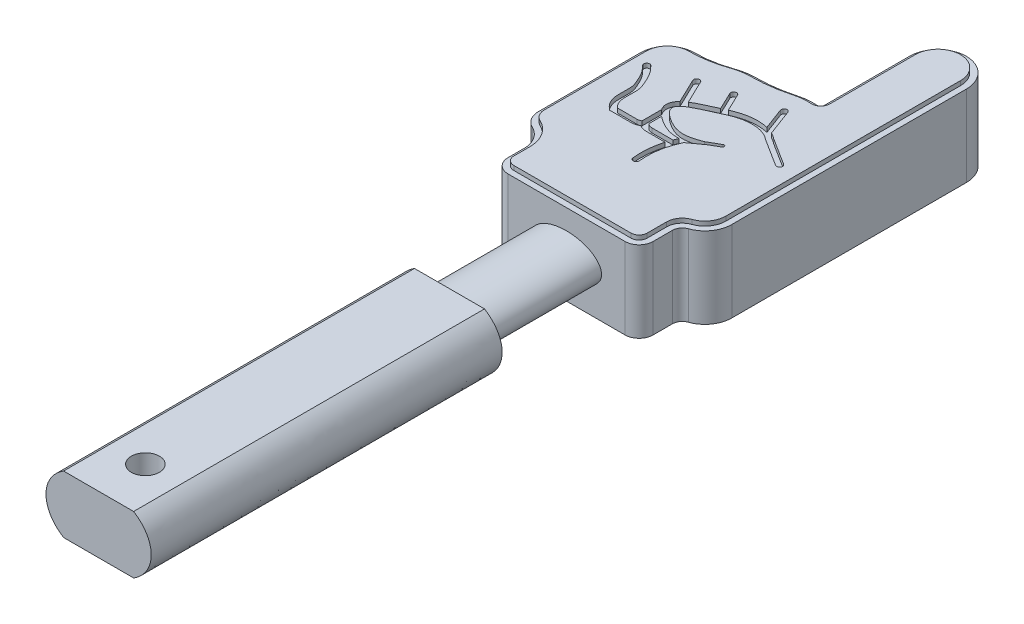
SolidWorks part; units mm, degrees
ref_plane "Plan de face" through (0, 0, 0) normal (0, 0, 1) x (1, 0, 0)
ref_plane "Plan de dessus" through (0, 0, 0) normal (0, 1, 0) x (1, 0, 0)
ref_plane "Plan de droite" through (0, 0, 0) normal (1, 0, 0) x (0, 0, -1)
sketch "Esquisse2" plane through (0, 0, 0) normal (0, 1, 0) x (1, 0, 0)
  line L4 (-461.3514, 50.6784) -> (-461.3514, 90.7755)
  line L5 (-471.0713, 90.7755) -> (-471.0713, 76.1755)
  line L6 (-465.5648, 44.7364) -> (-465.5648, 41.4326)
  line L7 (-467.9625, 39.035) -> (-487.9825, 39.035)
  line L8 (-490.3801, 41.4326) -> (-490.3801, 44.1985)
  line L9 (-494.5966, 50.8393) -> (-494.5966, 68.3008)
  arc A17 (-461.3514, 90.7755) -> (-471.0713, 90.7755) centre (-466.2114, 90.7755) ccw
  arc A18 (-471.0713, 76.1755) -> (-471.6659, 75.6215) centre (-471.6268, 76.1755) cw
  arc A19 (-471.6659, 75.6215) -> (-474.8438, 75.3021) centre (-472.3289, 66.2484) ccw
  arc A20 (-461.3514, 50.6784) -> (-464.4333, 46.3321) centre (-465.9571, 50.6784) cw
  arc A21 (-464.4333, 46.3321) -> (-465.5648, 44.7364) centre (-463.8739, 44.7364) ccw
  arc A22 (-465.5648, 41.4326) -> (-467.9625, 39.035) centre (-467.9625, 41.4326) cw
  arc A23 (-487.9825, 39.035) -> (-490.3801, 41.4326) centre (-487.9825, 41.4326) cw
  arc A24 (-490.3801, 44.1985) -> (-492.803, 48.0144) centre (-494.5966, 44.1985) ccw
  arc A25 (-492.803, 48.0144) -> (-494.5966, 50.8393) centre (-491.4751, 50.8393) cw
  arc A26 (-494.5966, 68.3008) -> (-489.9856, 72.9117) centre (-489.9856, 68.3008) cw
  arc A27 (-489.9856, 72.9117) -> (-484.1893, 73.9115) centre (-489.9856, 90.214) ccw
  arc A28 (-484.1893, 73.9115) -> (-480.9635, 74.4679) centre (-480.9635, 64.8387) cw
  arc A29 (-480.9635, 74.4679) -> (-474.8438, 75.3021) centre (-480.9635, 97.3326) ccw
  dimension "D3" = 14.6
  dimension "D4" = 0.5554
  dimension "D5" = 9.3965
  dimension "D6" = 4.6057
  dimension "D7" = 1.6909
  dimension "D8" = 2.3977
  dimension "D9" = 4.2164
  dimension "D10" = 3.1214
  dimension "D11" = 4.6109
  dimension "D12" = 17.3023
  dimension "D13" = 9.6292
  dimension "D1" = 9.72
  dimension "D2" = 461.3514
  dimension "D15" = 472.3289
  dimension "D16" = 465.5648
  dimension "D17" = 480.9635
  dimension "D18" = 484.1893
  dimension "D19" = 72.9117
  dimension "D21" = 50.8393
  dimension "D22" = 50.6784
  dimension "D36" = 39.035
extrude "Boss.-Extru.1" add sketch "Esquisse2" along normal blind 14.6
sketch "Esquisse4" plane through (0, 14.6, 0) normal (0, 1, 0) x (1, 0, 0)
  line L0 (-472.4313, 71.3413) -> (-470.759, 66.8763)
  line L1 (-479.2673, 69.577) -> (-477.8287, 66.5691)
  line L2 (-484.8272, 68.1421) -> (-483.1754, 64.6884)
  line L3 (-487.6052, 57.4055) -> (-484.2817, 57.4055)
  line L5 (-478.1514, 57.4055) -> (-481.7388, 57.4055)
  line L6 (-490.4583, 65.8897) -> (-491.0481, 66.5366)
  line L7 (-491.0481, 66.5366) -> (-472.4313, 71.3413) construction
  line L8 (-461.3514, 50.6784) -> (-461.3514, 90.7755) construction
  line L9 (-473.3677, 70.9906) -> (-471.9932, 67.3203)
  line L10 (-480.1694, 69.1456) -> (-478.7397, 66.1562)
  line L12 (-491.1972, 65.2159) -> (-491.787, 65.8628)
  line L13 (-487.9601, 56.4055) -> (-484.2783, 56.4055)
  line L14 (-477.4426, 56.4055) -> (-481.7388, 56.4055)
  line L16 (-483.1205, 57.4055) -> (-483.1205, 61.028) construction
  line L17 (-483.6205, 57.5979) -> (-483.6205, 60.9564)
  line L18 (-484.8272, 68.1421) -> (-482.7323, 63.7919) construction
  line L19 (-484.3767, 68.359) -> (-482.4341, 64.3251)
  line L20 (-485.2777, 67.9251) -> (-483.2443, 63.7026)
  line L21 (-470.3753, 65.4409) -> (-465.3514, 62.8537) construction
  line L22 (-469.8136, 66.2662) -> (-465.0842, 63.2763)
  line L23 (-470.348, 65.421) -> (-465.6185, 62.4311)
  line L24 (-473.0349, 60.7918) -> (-475.4776, 59.3877) construction
  line L25 (-472.8992, 60.5556) -> (-474.5084, 59.6306)
  line L26 (-473.1707, 61.028) -> (-475.2006, 59.8612)
  line L27 (-482.6205, 57.7552) -> (-482.6205, 59.9234)
  arc A0 (-484.2817, 57.4055) -> (-483.6205, 57.5979) centre (-484.2916, 58.6719) ccw
  arc A1 (-476.8297, 57.9491) -> (-477.9359, 51.4698) centre (-466.0442, 52.7736) ccw
  arc A3 (-481.7388, 57.4055) -> (-482.6205, 57.7552) centre (-481.7388, 58.692) cw
  arc A5 (-484.2783, 56.4055) -> (-483.0183, 56.797) centre (-484.2916, 58.6719) ccw
  arc A6 (-481.7388, 56.4055) -> (-483.0183, 56.797) centre (-481.7388, 58.692) cw
  arc A7 (-477.8343, 58.1619) -> (-478.1514, 57.4055) centre (-466.0442, 52.7736) ccw
  arc A8 (-472.4313, 71.3413) -> (-473.3677, 70.9906) centre (-472.8995, 71.1659) ccw
  arc A10 (-479.2673, 69.577) -> (-480.1694, 69.1456) centre (-479.7183, 69.3613) ccw
  arc A14 (-491.0481, 66.5366) -> (-491.787, 65.8628) centre (-491.4176, 66.1997) ccw
  arc A18 (-470.4025, 65.4609) -> (-470.348, 65.421) centre (-470.3753, 65.4409) ccw
  arc A19 (-477.9359, 51.4698) -> (-478.93, 51.3609) centre (-478.433, 51.4154) cw
  arc A21 (-484.3767, 68.359) -> (-485.2777, 67.9251) centre (-484.8272, 68.1421) ccw
  arc A23 (-470.4025, 65.4609) -> (-470.348, 65.421) centre (-470.3753, 65.4409) ccw
  arc A24 (-465.6185, 62.4311) -> (-465.0842, 63.2763) centre (-465.3514, 62.8537) ccw
  arc A25 (-472.8992, 60.5556) -> (-473.1707, 61.028) centre (-473.0349, 60.7918) ccw
  arc A27 (-478.488, 56.4055) -> (-478.93, 51.3609) centre (-466.0442, 52.7736) ccw
  spline S0 degree 3 poles (-490.4583, 65.8897) (-489.9643, 65.3478) (-489.2576, 64.0084) (-488.0431, 61.1753) (-489.0579, 58.5852) (-487.6052, 57.4055) knots 0 0 0 0 0.249547 0.474449 1 1 1 1
  spline S1 degree 3 poles (-483.1823, 64.7264) (-483.18, 64.7137) (-483.1777, 64.7011) (-483.1754, 64.6884) knots 0.246141 0.246141 0.246141 0.246141 0.248714 0.248714 0.248714 0.248714
  spline S2 degree 3 poles (-470.4025, 65.4609) (-471.657, 66.5152) (-475.3225, 66.8063) (-478.8719, 64.9069) (-484.364, 62.5575) (-480.7126, 59.6038) (-478.2259, 58.8088) (-475.901, 59.5831) (-475.2006, 59.8612) knots 0 0 0 0 0.163612 0.32751 0.477242 0.563601 0.697734 0.765481 0.765481 0.765481 0.765481
  spline S3 degree 2 poles (-474.5084, 59.6306) (-475.3996, 58.9745) (-476.8297, 57.9491) knots 0.955294 0.955294 0.955294 1 1 1
  spline S4 degree 3 poles (-483.2443, 63.7026) (-483.4189, 63.536) (-483.7603, 63.1422) (-484.042, 62.4144) (-483.9809, 61.7052) (-483.8197, 61.2849) (-483.6856, 61.0541) (-483.6205, 60.9564) knots 0.428302 0.428302 0.428302 0.428302 0.447364 0.468667 0.479319 0.48997 0.498689 0.498689 0.498689 0.498689
  spline S5 degree 3 poles (-478.7397, 66.1562) (-478.841, 66.109) (-479.3545, 65.8687) (-480.3361, 65.4112) (-481.5724, 64.8367) (-482.2436, 64.4471) (-482.4341, 64.3251) knots 0.287644 0.287644 0.287644 0.287644 0.298243 0.340849 0.383455 0.401257 0.401257 0.401257 0.401257
  spline S6 degree 3 poles (-491.1972, 65.2159) (-491.0951, 65.1039) (-490.914, 64.8749) (-490.5473, 64.3017) (-490.1129, 63.4322) (-489.672, 62.4162) (-489.5049, 61.5865) (-489.5458, 60.4567) (-489.5779, 59.3459) (-489.4093, 58.37) (-489.1649, 57.7435) (-488.8551, 57.2619) (-488.58, 56.9296) (-488.2037, 56.5974) (-488.0493, 56.478) (-487.9601, 56.4055) knots 0 0 0 0 0.064576 0.129153 0.258306 0.387458 0.516611 0.645764 0.774917 0.839493 0.90407 0.936358 0.968646 1.000934 1.033223 1.033223 1.033223 1.033223
  spline S7 degree 3 poles (-471.9932, 67.3203) (-472.1805, 67.365) (-473.344, 67.5872) (-475.4797, 67.4725) (-477.0435, 66.9088) (-477.8287, 66.5691) knots 0.068798 0.068798 0.068798 0.068798 0.085212 0.170424 0.255222 0.255222 0.255222 0.255222
  spline S8 degree 3 poles (-469.7591, 66.2264) (-470.0622, 66.4812) (-470.4037, 66.6993) (-470.759, 66.8763) knots 0 0 0 0 0.03228 0.03228 0.03228 0.03228
  spline S9 degree 3 poles (-482.6205, 59.9234) (-482.4376, 59.7779) (-481.8068, 59.3219) (-480.7516, 58.706) (-479.3663, 58.2092) (-478.3366, 58.1325) (-477.8343, 58.1619) knots 0.535686 0.535686 0.535686 0.535686 0.553879 0.596485 0.639091 0.681698 0.681698 0.681698 0.681698
  point P38 (-483.7797, 65.967)
  point P58 (-483.1205, 59.2167)
  point P61 (-474.2563, 60.0898)
  point P67 (-467.7161, 64.3487)
  dimension "D4" = 1.2865
  dimension "D6" = 4.6928
  dimension "D9" = 2.2865
  dimension "D10" = 11.0799
  dimension "D11" = 11.1625
  dimension "D13" = 13.661
  dimension "D1" = 1.2664
  dimension "D2" = 11.963
  dimension "D5" = 0.5
  dimension "D7" = 2.2664
  dimension "D12" = 0.0338
  dimension "D15" = 0.2724
  dimension "D8" = 1
  dimension "D14" = 15.4783
  dimension "D16" = 16.0443
  dimension "D17" = 3.7328
  dimension "D18" = 16.5846
  dimension "D19" = 17.9159
  dimension "D20" = 18.1649
  dimension "D21" = 1
  dimension "D22" = 20.3874
  dimension "D23" = 21.6423
  dimension "D24" = 4
  dimension "D25" = 21.824
  dimension "D26" = 5.1377
  dimension "D27" = 4.2671
  dimension "D28" = 23.4758
  dimension "D29" = 26.2538
  dimension "D30" = 27.0797
  dimension "D31" = 27.2299
  dimension "D32" = 27.9056
  dimension "D33" = 29.1069
  dimension "D34" = 29.6967
  dimension "D35" = 12.8812
  dimension "D36" = 13.8294
  dimension "D37" = 6.3647
  dimension "D38" = 8.4077
  dimension "D39" = 17.6054
  dimension "D40" = 18.3562
  dimension "D41" = 8.4623
  dimension "D42" = 9.0239
  dimension "D43" = 19.5575
  dimension "D44" = 11.5481
  dimension "D45" = 16.0912
  dimension "D46" = 9.4077
  dimension "D47" = 10.6418
  dimension "D48" = 11.5478
  dimension "D49" = 18.3669
  dimension "D50" = 11.6836
  dimension "D51" = 11.8193
  dimension "D52" = 21.2691
  dimension "D53" = 12.9049
  dimension "D54" = 13.157
  dimension "D55" = 13.8492
  dimension "D56" = 21.6669
  dimension "D57" = 16.4773
  dimension "D58" = 16.4829
  dimension "D59" = 23.0253
  dimension "D60" = 30.0662
  dimension "D61" = 12.8846
  dimension "D62" = 17.3883
  dimension "D63" = 16.099
  dimension "D64" = 12.3497
  dimension "D65" = 18.3943
  dimension "D66" = 19.8742
  dimension "D67" = 21.0827
  dimension "D70" = 21.7691
  dimension "D71" = 21.8309
  dimension "D72" = 21.8929
  dimension "D73" = 13.5913
  dimension "D74" = 22.4283
  dimension "D75" = 13.7576
  dimension "D79" = 15.6533
  dimension "D80" = 26.6087
  dimension "D84" = 18.0165
  dimension "D90" = 19.8943
  dimension "D92" = 20.076
extrude "Cut-Extrude1" cut sketch "Esquisse4" against normal blind 0.75
sketch "Sketch1" plane through (0, 14.6, 0) normal (0, 1, 0) x (1, 0, 0)
  line L0 (-462.3514, 50.6784) -> (-462.3514, 90.7755)
  line L1 (-470.0713, 90.7755) -> (-470.0713, 76.1755)
  line L2 (-493.5966, 68.3008) -> (-493.5966, 50.8393)
  line L3 (-489.3801, 44.1985) -> (-489.3801, 41.4326)
  line L4 (-487.9825, 40.035) -> (-467.9625, 40.035)
  line L5 (-466.5648, 41.4326) -> (-466.5648, 44.7364)
  line L6 (-461.3514, 50.6784) -> (-461.3514, 90.7755)
  line L7 (-471.0713, 90.7755) -> (-471.0713, 76.1755)
  line L8 (-494.5966, 68.3008) -> (-494.5966, 50.8393)
  line L9 (-490.3801, 44.1985) -> (-490.3801, 41.4326)
  line L10 (-487.9825, 39.035) -> (-467.9625, 39.035)
  line L11 (-465.5648, 41.4326) -> (-465.5648, 44.7364)
  line L12 (-461.3514, 50.6784) -> (-461.3514, 90.7755)
  line L13 (-471.0713, 90.7755) -> (-471.0713, 76.1755)
  line L14 (-494.5966, 68.3008) -> (-494.5966, 50.8393)
  line L15 (-490.3801, 44.1985) -> (-490.3801, 41.4326)
  line L16 (-487.9825, 39.035) -> (-467.9625, 39.035)
  line L17 (-465.5648, 41.4326) -> (-465.5648, 44.7364)
  arc A0 (-464.7642, 47.2758) -> (-462.3514, 50.6784) centre (-465.9571, 50.6784) ccw
  arc A1 (-462.3514, 90.7755) -> (-470.0713, 90.7755) centre (-466.2114, 90.7755) ccw
  arc A2 (-471.7365, 74.624) -> (-470.0713, 76.1755) centre (-471.6268, 76.1755) ccw
  arc A3 (-471.7365, 74.624) -> (-474.5762, 74.3386) centre (-472.3289, 66.2484) ccw
  arc A4 (-480.9635, 73.4679) -> (-474.5762, 74.3386) centre (-480.9635, 97.3326) ccw
  arc A5 (-480.9635, 73.4679) -> (-483.8543, 72.9693) centre (-480.9635, 64.8387) ccw
  arc A6 (-489.9856, 71.9117) -> (-483.8543, 72.9693) centre (-489.9856, 90.214) ccw
  arc A7 (-489.9856, 71.9117) -> (-493.5966, 68.3008) centre (-489.9856, 68.3008) ccw
  arc A8 (-493.5966, 50.8393) -> (-492.3776, 48.9194) centre (-491.4751, 50.8393) ccw
  arc A9 (-489.3801, 44.1985) -> (-492.3776, 48.9194) centre (-494.5966, 44.1985) ccw
  arc A10 (-489.3801, 41.4326) -> (-487.9825, 40.035) centre (-487.9825, 41.4326) ccw
  arc A11 (-467.9625, 40.035) -> (-466.5648, 41.4326) centre (-467.9625, 41.4326) ccw
  arc A12 (-464.7642, 47.2758) -> (-466.5648, 44.7364) centre (-463.8739, 44.7364) ccw
  arc A13 (-464.4333, 46.3321) -> (-461.3514, 50.6784) centre (-465.9571, 50.6784) ccw
  arc A14 (-461.3514, 90.7755) -> (-471.0713, 90.7755) centre (-466.2114, 90.7755) ccw
  arc A15 (-471.6659, 75.6215) -> (-471.0713, 76.1755) centre (-471.6268, 76.1755) ccw
  arc A16 (-471.6659, 75.6215) -> (-474.8438, 75.3021) centre (-472.3289, 66.2484) ccw
  arc A17 (-480.9635, 74.4679) -> (-474.8438, 75.3021) centre (-480.9635, 97.3326) ccw
  arc A18 (-480.9635, 74.4679) -> (-484.1893, 73.9115) centre (-480.9635, 64.8387) ccw
  arc A19 (-489.9856, 72.9117) -> (-484.1893, 73.9115) centre (-489.9856, 90.214) ccw
  arc A20 (-489.9856, 72.9117) -> (-494.5966, 68.3008) centre (-489.9856, 68.3008) ccw
  arc A21 (-494.5966, 50.8393) -> (-492.803, 48.0144) centre (-491.4751, 50.8393) ccw
  arc A22 (-490.3801, 44.1985) -> (-492.803, 48.0144) centre (-494.5966, 44.1985) ccw
  arc A23 (-490.3801, 41.4326) -> (-487.9825, 39.035) centre (-487.9825, 41.4326) ccw
  arc A24 (-467.9625, 39.035) -> (-465.5648, 41.4326) centre (-467.9625, 41.4326) ccw
  arc A25 (-464.4333, 46.3321) -> (-465.5648, 44.7364) centre (-463.8739, 44.7364) ccw
  arc A26 (-464.4333, 46.3321) -> (-461.3514, 50.6784) centre (-465.9571, 50.6784) ccw
  arc A27 (-461.3514, 90.7755) -> (-471.0713, 90.7755) centre (-466.2114, 90.7755) ccw
  arc A28 (-471.6659, 75.6215) -> (-471.0713, 76.1755) centre (-471.6268, 76.1755) ccw
  arc A29 (-471.6659, 75.6215) -> (-474.8438, 75.3021) centre (-472.3289, 66.2484) ccw
  arc A30 (-480.9635, 74.4679) -> (-474.8438, 75.3021) centre (-480.9635, 97.3326) ccw
  arc A31 (-480.9635, 74.4679) -> (-484.1893, 73.9115) centre (-480.9635, 64.8387) ccw
  arc A32 (-489.9856, 72.9117) -> (-484.1893, 73.9115) centre (-489.9856, 90.214) ccw
  arc A33 (-489.9856, 72.9117) -> (-494.5966, 68.3008) centre (-489.9856, 68.3008) ccw
  arc A34 (-494.5966, 50.8393) -> (-492.803, 48.0144) centre (-491.4751, 50.8393) ccw
  arc A35 (-490.3801, 44.1985) -> (-492.803, 48.0144) centre (-494.5966, 44.1985) ccw
  arc A36 (-490.3801, 41.4326) -> (-487.9825, 39.035) centre (-487.9825, 41.4326) ccw
  arc A37 (-467.9625, 39.035) -> (-465.5648, 41.4326) centre (-467.9625, 41.4326) ccw
  arc A38 (-464.4333, 46.3321) -> (-465.5648, 44.7364) centre (-463.8739, 44.7364) ccw
  dimension "D1" = 0
  dimension "D2" = 1
extrude "Cut-Extrude2" cut sketch "Sketch1" against normal blind 0.75
sketch "Sketch3" plane through (0, 0, -39.035) normal (0, 0, 1) x (1, 0, 0)
  line L0 (-487.9825, 13.85) -> (-467.9625, 13.85) construction
  line L1 (-487.9825, 13.85) -> (-487.9825, 0) construction
  ellipse E0 centre (-477.9825, 6.925) end of major axis (-483.9825, 6.925) minor radius 3.5
  point P1 (-472.0851, 6.925)
  point P7 (-477.9825, 3.2328)
  dimension "D1" = 6.925
  dimension "D2" = 10
  dimension "D3" = 7
  dimension "D4" = 12
extrude "Boss-Extrude1" add sketch "Sketch3" along normal blind 20
sketch "Sketch4" plane through (0, 0, -19.035) normal (0, 0, 1) x (1, 0, 0)
  line L0 (-471.9948, 11.85) -> (-483.9702, 11.85)
  line L2 (-483.9702, 2) -> (-471.9948, 2)
  line L4 (-487.9825, 0) -> (-467.9625, 0) construction
  line L5 (-487.9825, 13.85) -> (-467.9625, 13.85) construction
  spline S0 degree 3 poles (-468.9825, 6.6655) (-468.9825, 7.4441) (-469.0613, 7.9493) (-469.2911, 8.6876) (-469.3866, 8.9297) (-469.6081, 9.3925) (-469.7346, 9.6152) (-470.0172, 10.0444) (-470.1743, 10.2518) (-470.5098, 10.6425) (-470.6884, 10.8265) (-471.254, 11.3483) (-471.6739, 11.6572) (-472.549, 12.1865) (-473.0071, 12.4102) (-473.9577, 12.7896) (-474.4523, 12.9451) (-475.9405, 13.3093) (-476.9509, 13.4246) (-478.4914, 13.4252) (-479.0046, 13.3955) (-480.0155, 13.2773) (-480.5156, 13.1888) (-481.5037, 12.9476) (-481.9939, 12.7943) (-482.9511, 12.4135) (-483.4109, 12.1891) (-484.0672, 11.7928) (-484.2804, 11.6507) (-484.6942, 11.3436) (-484.8944, 11.1788) (-485.4603, 10.6577) (-485.7964, 10.2723) (-486.3679, 9.4084) (-486.5908, 8.9479) (-486.8211, 8.2181) (-486.8808, 7.9663) (-486.9612, 7.4547) (-486.9815, 7.1991) (-486.9834, 6.6879) (-486.965, 6.4323) (-486.8886, 5.9215) (-486.8304, 5.6677) (-486.6793, 5.1772) (-486.586, 4.9383) (-486.3652, 4.4729) (-486.237, 4.2457) (-485.9548, 3.8152) (-485.8002, 3.6103) (-485.4663, 3.2195) (-485.2859, 3.0327) (-484.7177, 2.5067) (-484.3064, 2.2034) (-483.432, 1.672) (-482.9649, 1.443) (-482.0139, 1.0627) (-481.5279, 0.9094) (-480.5381, 0.6656) (-480.0333, 0.5752) (-479.0103, 0.4547) (-478.4994, 0.4253) (-477.4788, 0.4247) (-476.9691, 0.4536) (-475.951, 0.5723) (-475.4412, 0.6627) (-474.4482, 0.906) (-473.9619, 1.059) (-473.2502, 1.3427) (-473.0159, 1.4463) (-472.5539, 1.6739) (-472.3265, 1.7979) (-471.668, 2.1967) (-471.2562, 2.4998) (-470.6888, 3.023) (-470.5075, 3.21) (-470.1728, 3.6001) (-470.0182, 3.8042) (-469.5955, 4.4455) (-469.367, 4.9188) (-469.1391, 5.6502) (-469.0812, 5.8986) (-469.0028, 6.4053) (-468.9825, 6.6655) (-468.9825, 7.4441) (-469.0613, 7.9493) knots -0.015625 -0.015625 0 0 0.03125 0.03125 0.046875 0.046875 0.0625 0.0625 0.078125 0.078125 0.09375 0.09375 0.125 0.125 0.15625 0.15625 0.1875 0.1875 0.25 0.25 0.28125 0.28125 0.3125 0.3125 0.34375 0.34375 0.375 0.375 0.390625 0.390625 0.40625 0.40625 0.4375 0.4375 0.46875 0.46875 0.484375 0.484375 0.5 0.5 0.515625 0.515625 0.53125 0.53125 0.546875 0.546875 0.5625 0.5625 0.578125 0.578125 0.59375 0.59375 0.625 0.625 0.65625 0.65625 0.6875 0.6875 0.71875 0.71875 0.75 0.75 0.78125 0.78125 0.8125 0.8125 0.84375 0.84375 0.859375 0.859375 0.875 0.875 0.90625 0.90625 0.921875 0.921875 0.9375 0.9375 0.96875 0.96875 0.984375 0.984375 1 1 1.03125 1.03125 1.046875 only from (-468.9825, 6.925) to (-468.9825, 6.925)
  spline S1 degree 3 poles (-483.9702, 11.85) (-484.1465, 11.7394) (-484.319, 11.6221) (-484.6942, 11.3436) (-484.8944, 11.1788) (-485.4603, 10.6577) (-485.7964, 10.2723) (-486.3679, 9.4084) (-486.5908, 8.9479) (-486.8211, 8.2181) (-486.8808, 7.9663) (-486.9612, 7.4547) (-487.0018, 6.9434) (-486.965, 6.4323) (-486.8886, 5.9215) (-486.8304, 5.6677) (-486.6793, 5.1772) (-486.586, 4.9383) (-486.3652, 4.4729) (-486.237, 4.2457) (-485.9548, 3.8152) (-485.8002, 3.6103) (-485.4663, 3.2195) (-485.2859, 3.0327) (-484.747, 2.5339) (-484.3698, 2.2506) (-483.9702, 2) knots 0.377913 0.377913 0.377913 0.377913 0.390625 0.390625 0.40625 0.40625 0.4375 0.4375 0.46875 0.46875 0.484375 0.484375 0.5 0.515625 0.515625 0.53125 0.53125 0.546875 0.546875 0.5625 0.5625 0.578125 0.578125 0.59375 0.59375 0.622583 0.622583 0.622583 0.622583
  spline S2 degree 3 poles (-471.9948, 2) (-471.5977, 2.249) (-471.2238, 2.5297) (-470.6888, 3.023) (-470.5075, 3.21) (-470.1728, 3.6001) (-470.0182, 3.8042) (-469.5955, 4.4455) (-469.367, 4.9188) (-469.1391, 5.6502) (-469.0812, 5.8986) (-469.0028, 6.4053) (-468.9825, 6.6655) (-468.9825, 7.4441) (-469.0613, 7.9493) (-469.2911, 8.6876) (-469.3866, 8.9297) (-469.6081, 9.3925) (-469.7346, 9.6152) (-470.0172, 10.0444) (-470.1743, 10.2518) (-470.5098, 10.6425) (-470.6884, 10.8265) (-471.2204, 11.3173) (-471.5993, 11.6018) (-471.9948, 11.85) knots 0.877677 0.877677 0.877677 0.877677 0.90625 0.90625 0.921875 0.921875 0.9375 0.9375 0.96875 0.96875 0.984375 0.984375 1 1 1.03125 1.03125 1.046875 1.046875 1.0625 1.0625 1.078125 1.078125 1.09375 1.09375 1.122213 1.122213 1.122213 1.122213
  dimension "D2" = 2
  dimension "D3" = 2
  dimension "D1" = 3
extrude "Boss-Extrude4" add sketch "Sketch4" along normal blind 60
sketch "Sketch5" plane through (0, 11.85, 0) normal (0, 1, 0) x (1, 0, 0)
  line L0 (-483.9702, -32.965) -> (-471.9948, -32.965) construction
  line L1 (-483.9702, -40.965) -> (-483.9702, 19.035) construction
  line L2 (-471.9948, -40.965) -> (-471.9948, 19.035) construction
  line L3 (-477.9825, -40.965) -> (-477.9825, -32.965) construction
  line L4 (-471.9948, -40.965) -> (-483.9702, -40.965) construction
  circle A0 centre (-477.9825, -32.965) radius 2.4
  point P12 (-477.3855, -28.8363)
  dimension "D1" = 4.8
  dimension "D2" = 8
extrude "Cut-Extrude3" cut sketch "Sketch5" against normal through all
